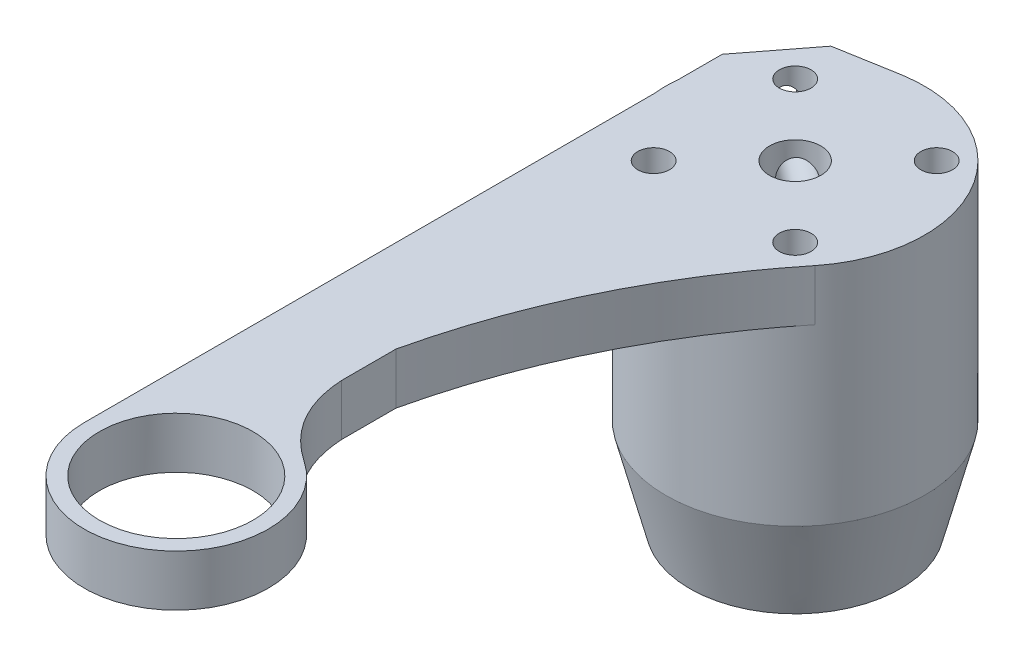
SolidWorks part; units mm, degrees
ref_plane "Płaszczyzna przednia" through (0, 0, 0) normal (0, 0, 1) x (1, 0, 0)
ref_plane "Płaszczyzna górna" through (0, 0, 0) normal (0, 1, 0) x (1, 0, 0)
ref_plane "Płaszczyzna prawa" through (0, 0, 0) normal (1, 0, 0) x (0, 0, -1)
sketch "Szkic1" plane through (0, 0, 0) normal (0, 1, 0) x (1, 0, 0)
  line L0 (-9, 0) -> (-9, 55.6005)
  line L2 (0, 16.16) -> (0, 21.46)
  line L3 (-9, 0) -> (0, 0) construction
  line L4 (-9, 0) -> (-9, 55.6005) construction
  line L7 (-9, 16.16) -> (-9, 31.04) construction
  line L9 (-9, 31.04) -> (-9, 53.0606) construction
  arc A0 (-9, 0) -> (5.0273, 7.465) centre (0, 0) ccw
  arc A1 (13.3936, 48.9622) -> (-9, 55.6005) centre (3.56, 56.88) ccw
  spline S0 degree 2 poles (0, 16.16) (0.3108, 10.6467) (5.0273, 7.465) knots 0 0 0 1 1 1
  spline S1 degree 2 poles (0, 21.46) (3.4789, 36.6218) (13.3936, 48.9622) knots 0 0 0 1 1 1
  dimension "D1" = 18
  dimension "D6" = 25.25
  dimension "D3" = 9
  dimension "D5" = 5.3
  dimension "D9" = 56.88
extrude "Dodanie-wyciągnięcie1" add sketch "Szkic1" along normal blind 5
sketch "Szkic3" plane through (0, 0, 0) normal (0, -1, 0) x (1, 0, 0)
  circle A0 centre (3.56, -56.88) radius 12.625
extrude "Dodanie-wyciągnięcie2" add sketch "Szkic3" along normal blind 17
sketch "Szkic4" plane through (0, -17, 0) normal (0, -1, 0) x (1, 0, 0)
  line L0 (3.56, -56.88) -> (3.56, -49.97) construction
  line L1 (3.56, -56.88) -> (3.56, -63.79) construction
  line L2 (3.56, -63.79) -> (-3.35, -63.79) construction
  line L3 (3.56, -63.79) -> (10.47, -63.79) construction
  line L4 (3.56, -49.97) -> (10.47, -49.97) construction
  line L5 (10.47, -49.97) -> (-3.35, -49.97) construction
  circle A0 centre (3.56, -56.88) radius 2.5
  circle A1 centre (-3.35, -49.97) radius 1.55
  circle A2 centre (10.47, -49.97) radius 1.55
  circle A3 centre (-3.35, -63.79) radius 1.55
  circle A4 centre (10.47, -63.79) radius 1.55
  dimension "D1" = 5
  dimension "D6" = 3.1
  dimension "D7" = 3.1
  dimension "D8" = 3.1
  dimension "D9" = 3.1
  dimension "D2" = 6.91
  dimension "D3" = 6.91
  dimension "D4" = 6.91
  dimension "D5" = 6.91
extrude "Wytnij-wyciągnięcie1" cut sketch "Szkic4" against normal blind 25
sketch "Szkic5" plane through (0, -17, 0) normal (0, -1, 0) x (1, 0, 0)
  circle A0 centre (3.56, -56.88) radius 3.75
  dimension "D1" = 7.5
extrude "Wytnij-wyciągnięcie2" cut sketch "Szkic5" against normal blind 7.5
sketch "Szkic6" plane through (0, 5, 0) normal (0, 1, 0) x (1, 0, 0)
  line L0 (-9, 55.6005) -> (-9, 62.3105)
  line L1 (-9, 62.3105) -> (-4.3794, 68.3105)
  line L2 (-4.3794, 68.3105) -> (1.5606, 69.3457)
  arc A0 (13.3936, 48.9622) -> (-9, 55.6005) centre (3.56, 56.88) ccw construction
  spline S0 degree 2 poles (1.5606, 69.3457) (-7.2841, 65.5314) (-9, 55.6005) knots 0 0 0 1 1 1
  dimension "D1" = 6.71
  dimension "D2" = 6
  dimension "D3" = 5.94
  dimension "D4" = 142.4
extrude "Dodanie-wyciągnięcie3" add sketch "Szkic6" against normal blind 15
sketch "Szkic7" plane through (-35.7711, 0, -27.5475) normal (-0.7923, 0, -0.6101) x (-0.6101, 0, 0.7923)
  line L0 (-51.4497, 5) -> (-43.8767, 5) construction
  line L1 (-47.6632, 5) -> (-47.6632, 2) construction
  line L2 (-47.6632, 2) -> (-47.6632, -7) construction
  circle A0 centre (-47.6632, 2) radius 1.5
  circle A1 centre (-47.6632, -7) radius 1.5
  dimension "D3" = 3
  dimension "D4" = 3
  dimension "D1" = 3
  dimension "D2" = 9
extrude "Wytnij-wyciągnięcie3" cut sketch "Szkic7" against normal blind 14
sketch "Szkic8" plane through (0, 5, 0) normal (0, 1, 0) x (1, 0, 0)
  circle A0 centre (0, 0) radius 7.5
  dimension "D1" = 15
extrude "Wytnij-wyciągnięcie4" cut sketch "Szkic8" against normal blind 14
sketch "Szkic14" plane through (0, -17, 0) normal (0, -1, 0) x (1, 0, 0)
  circle A0 centre (3.56, -56.88) radius 12.625
  dimension "D1" = 25.25
ref_plane "Płaszczyzna3" through (0, -26.05, 0) normal (0, -1, 0) x (-1, 0, 0)
sketch "Szkic16" plane through (0, -26.05, 0) normal (0, -1, 0) x (-1, 0, 0)
  circle A0 centre (-3.56, 56.88) radius 10.3
  dimension "D1" = 20.6
loft "Wyciągnięcie po profilach3" add profiles "Szkic14", "Szkic16"
sketch "Szkic18" plane through (0, -26.05, 0) normal (0, -1, 0) x (1, 0, 0)
  circle A0 centre (3.56, -56.88) radius 3.75
  dimension "D1" = 7.5
extrude "Wytnij-wyciągnięcie5" cut sketch "Szkic18" against normal blind 7.5
sketch "Szkic19" plane through (0, -26.05, 0) normal (0, -1, 0) x (1, 0, 0)
  line L0 (3.56, -56.88) -> (10.8, -56.88) construction
  line L1 (3.56, -56.88) -> (3.56, -49.64) construction
  line L2 (3.56, -56.88) -> (3.56, -64.12) construction
  line L3 (3.56, -56.88) -> (-3.68, -56.88) construction
  line L4 (-3.68, -56.88) -> (-3.68, -53.48) construction
  line L5 (-3.68, -56.88) -> (-3.68, -60.28) construction
  line L6 (3.56, -49.64) -> (0.16, -49.64) construction
  line L7 (3.56, -49.64) -> (6.96, -49.64) construction
  line L8 (10.8, -56.88) -> (10.8, -53.48) construction
  line L9 (10.8, -56.88) -> (10.8, -60.28) construction
  line L10 (3.56, -64.12) -> (6.96, -64.12) construction
  line L11 (3.56, -64.12) -> (0.16, -64.12) construction
  circle A0 centre (-3.68, -53.48) radius 0.7
  circle A1 centre (-3.68, -56.88) radius 0.7
  circle A2 centre (-3.68, -60.28) radius 0.7
  circle A3 centre (0.16, -64.12) radius 0.7
  circle A4 centre (3.56, -64.12) radius 0.7
  circle A5 centre (6.96, -64.12) radius 0.7
  circle A6 centre (10.8, -60.28) radius 0.7
  circle A7 centre (10.8, -56.88) radius 0.7
  circle A8 centre (10.8, -53.6394) radius 0.7
  circle A9 centre (6.96, -49.64) radius 0.7
  circle A10 centre (3.56, -49.64) radius 0.7
  circle A11 centre (0.16, -49.64) radius 0.7
  dimension "D13" = 1.4
  dimension "D14" = 1.4
  dimension "D15" = 1.4
  dimension "D16" = 1.4
  dimension "D17" = 1.4
  dimension "D18" = 1.4
  dimension "D19" = 1.4
  dimension "D20" = 1.4
  dimension "D21" = 1.4
  dimension "D22" = 1.4
  dimension "D23" = 1.4
  dimension "D24" = 1.4
  dimension "D1" = 7.24
  dimension "D2" = 7.24
  dimension "D3" = 7.24
  dimension "D4" = 7.24
  dimension "D5" = 3.4
  dimension "D6" = 3.4
  dimension "D7" = 3.4
  dimension "D8" = 3.4
  dimension "D9" = 3.4
  dimension "D10" = 3.4
  dimension "D11" = 3.4
  dimension "D12" = 3.4
extrude "Wytnij-wyciągnięcie6" cut sketch "Szkic19" against normal blind 5
